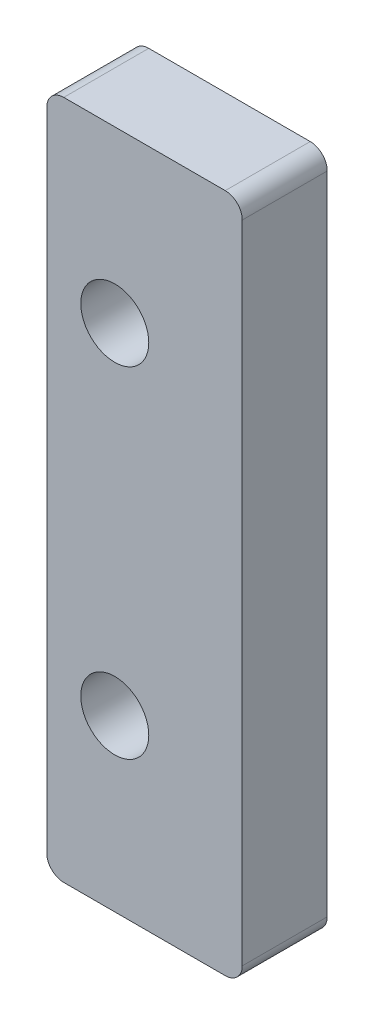
SolidWorks part; units mm, degrees
ref_plane "Front Plane" through (0, 0, 0) normal (0, 0, 1) x (1, 0, 0)
ref_plane "Top Plane" through (0, 0, 0) normal (0, 1, 0) x (1, 0, 0)
ref_plane "Right Plane" through (0, 0, 0) normal (1, 0, 0) x (0, 0, -1)
sketch "Sketch1" plane through (0, 0, 0) normal (0, 0, 1) x (1, 0, 0)
  line L0 (4, 40) -> (4, 0) construction
  line L1 (0, 0) -> (11.5, 0)
  line L2 (0, 0) -> (0, 40)
  line L3 (0, 40) -> (11.5, 40)
  line L4 (11.5, 0) -> (11.5, 40)
  circle A0 centre (4, 10) radius 2
  circle A1 centre (4, 30) radius 2
  dimension "D2" = 4
  dimension "D1" = 20
  dimension "D3" = 10
  dimension "D4" = 10
  dimension "D5" = 4
  dimension "D6" = 7.5
extrude "Boss-Extrude1" add sketch "Sketch1" along normal blind 5
fillet "Fillet1" radius 1 4 edges at (11.5, 0, 2.5) (0, 0, 2.5) (0, 40, 2.5) (11.5, 40, 2.5)
